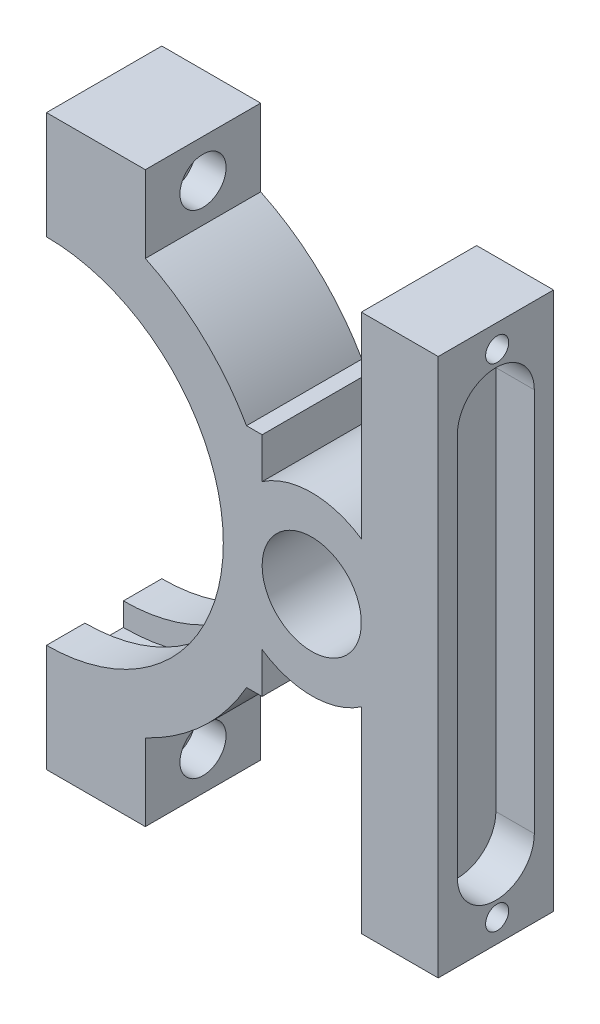
SolidWorks part; units mm, degrees
ref_plane "Front Plane" through (0, 0, 0) normal (0, 0, 1) x (1, 0, 0)
ref_plane "Top Plane" through (0, 0, 0) normal (0, 1, 0) x (1, 0, 0)
ref_plane "Right Plane" through (0, 0, 0) normal (1, 0, 0) x (0, 0, -1)
sketch "Sketch1" plane through (0, 0, 0) normal (0, 0, 1) x (1, 0, 0)
  line L0 (0, 23) -> (0, 37)
  line L1 (0, 37) -> (12.8595, 37)
  line L2 (12.8595, 37) -> (12.8595, 27)
  line L3 (0, 0) -> (90, 0) construction
  line L4 (26.0205, 14.7412) -> (28.0505, 14.7412)
  line L5 (28.0505, 25) -> (28.0505, -25) construction
  line L6 (28.0505, 14.7412) -> (28.0505, 9.4604)
  line L7 (40.9505, 9.4604) -> (40.9505, 35)
  line L8 (40.9505, 35) -> (50.9505, 35)
  line L9 (50.9505, 35) -> (50.9505, -35)
  line L10 (40.9505, -35) -> (50.9505, -35)
  line L11 (40.9505, -9.4604) -> (40.9505, -35)
  line L12 (28.0505, -14.7412) -> (28.0505, -9.4604)
  line L13 (26.0205, -14.7412) -> (28.0505, -14.7412)
  line L14 (12.8595, -37) -> (12.8595, -27)
  line L15 (0, -37) -> (12.8595, -37)
  line L16 (0, -23) -> (0, -37)
  arc A0 (0, 23) -> (0, -23) centre (0, 0) cw
  arc A1 (12.8595, 27) -> (26.0205, 14.7412) centre (0, 0) cw
  circle A2 centre (34.5005, 0) radius 6.45
  arc A3 (28.0505, 9.4604) -> (40.9505, 9.4604) centre (34.5005, 0) cw
  arc A4 (28.0505, -9.4604) -> (40.9505, -9.4604) centre (34.5005, 0) ccw
  arc A5 (12.8595, -27) -> (26.0205, -14.7412) centre (0, 0) ccw
  point P8 (28.0505, 0)
  point P19 (50.9505, 0)
  point P29 (40.9505, 0)
  dimension "D2" = 23
  dimension "D5" = 35
  dimension "D7" = 6.45
  dimension "D8" = 50
  dimension "D9" = 29.906
  dimension "D10" = 11.45
  dimension "D3" = 14
  dimension "D4" = 10
  dimension "D6" = 2.03
  dimension "D11" = 90
  dimension "D12" = 10
  dimension "D13" = 35
extrude "Boss-Extrude1" add sketch "Sketch1" along normal blind 15
ref_plane "Plane1" through (0, 0, 0) normal (-1, 0, 0) x (0, 0, 1)
sketch "Sketch2" plane through (0, 0, 0) normal (-1, 0, 0) x (0, 0, 1)
  line L0 (7.5, 37) -> (7.5, 23) construction
  line L1 (15, 37) -> (0, 37) construction
  line L2 (15, 23) -> (0, 23) construction
  line L3 (10, 26) -> (5, 26)
  line L4 (5, 26) -> (5, 23)
  line L5 (10, 26) -> (10, 23)
  line L6 (5, 23) -> (10, 23)
  line L7 (15, 0) -> (0, 0) construction
  line L8 (15, -23) -> (15, 23) construction
  point P10 (7.5, 26)
  dimension "D1" = 2.5
  dimension "D2" = 3
revolve "Cut-Revolve1" cut sketch "Sketch2" angle 360 about L7
ref_plane "Plane2" through (50.9505, 0, 0) normal (1, 0, 0) x (0, 0, -1)
sketch "Sketch3" plane through (50.9505, 0, 0) normal (1, 0, 0) x (0, 0, -1)
  line L0 (-15, 0) -> (0, 0) construction
  line L1 (-15, -35) -> (-15, 35) construction
  line L2 (-7.5, 35) -> (-7.5, -35) construction
  line L3 (-15, 35) -> (0, 35) construction
  line L5 (-15, -35) -> (0, -35) construction
  line L8 (-12.5, -25) -> (-12.5, 25)
  line L10 (-2.5, -25) -> (-2.5, 25)
  line L11 (-12.5, -25) -> (-2.5, 25) construction
  line L12 (-12.5, 25) -> (-2.5, -25) construction
  arc A0 (-12.5, 25) -> (-2.5, 25) centre (-7.5, 25) cw
  arc A1 (-12.5, -25) -> (-2.5, -25) centre (-7.5, -25) ccw
  point P14 (-7.5, 0)
  dimension "D1" = 50
  dimension "D2" = 10
extrude "Cut-Extrude3" cut sketch "Sketch3" against normal blind 5
ref_plane "Plane3" through (12.8595, 0, 0) normal (1, 0, 0) x (0, 0, -1)
sketch "Sketch4" plane through (12.8595, 0, 0) normal (1, 0, 0) x (0, 0, -1)
  line L0 (-7.5, 37) -> (-7.5, 27) construction
  line L1 (-15, 37) -> (0, 37) construction
  line L2 (-15, 27) -> (0, 27) construction
  line L3 (-15, 32) -> (0, 32) construction
  line L4 (-15, 27) -> (-15, 37) construction
  line L5 (0, 27) -> (0, 37) construction
  line L6 (-15, 0) -> (1.8408, 0) construction
  circle A0 centre (-7.3334, 32) radius 1.5
  circle A1 centre (-7.3334, -32) radius 1.5
  dimension "D1" = 3
extrude "Cut-Extrude4" cut sketch "Sketch4" against normal through all both and the other way through all contours A0 | A1
sketch "Sketch5" plane through (12.8595, 0, 0) normal (1, 0, 0) x (0, 0, -1)
  line L0 (-7.5, 37) -> (-7.5, 27) construction
  line L1 (-15, 37) -> (0, 37) construction
  line L2 (-15, 27) -> (0, 27) construction
  line L3 (-15, 32) -> (0, 32) construction
  line L4 (-15, 27) -> (-15, 37) construction
  line L5 (0, 27) -> (0, 37) construction
  line L6 (-15, 0) -> (6.1086, 0) construction
  circle A0 centre (-7.5, 32) radius 3
  circle A1 centre (-7.5, -32) radius 3
  dimension "D1" = 6
extrude "Cut-Extrude5" cut sketch "Sketch5" against normal blind 4
